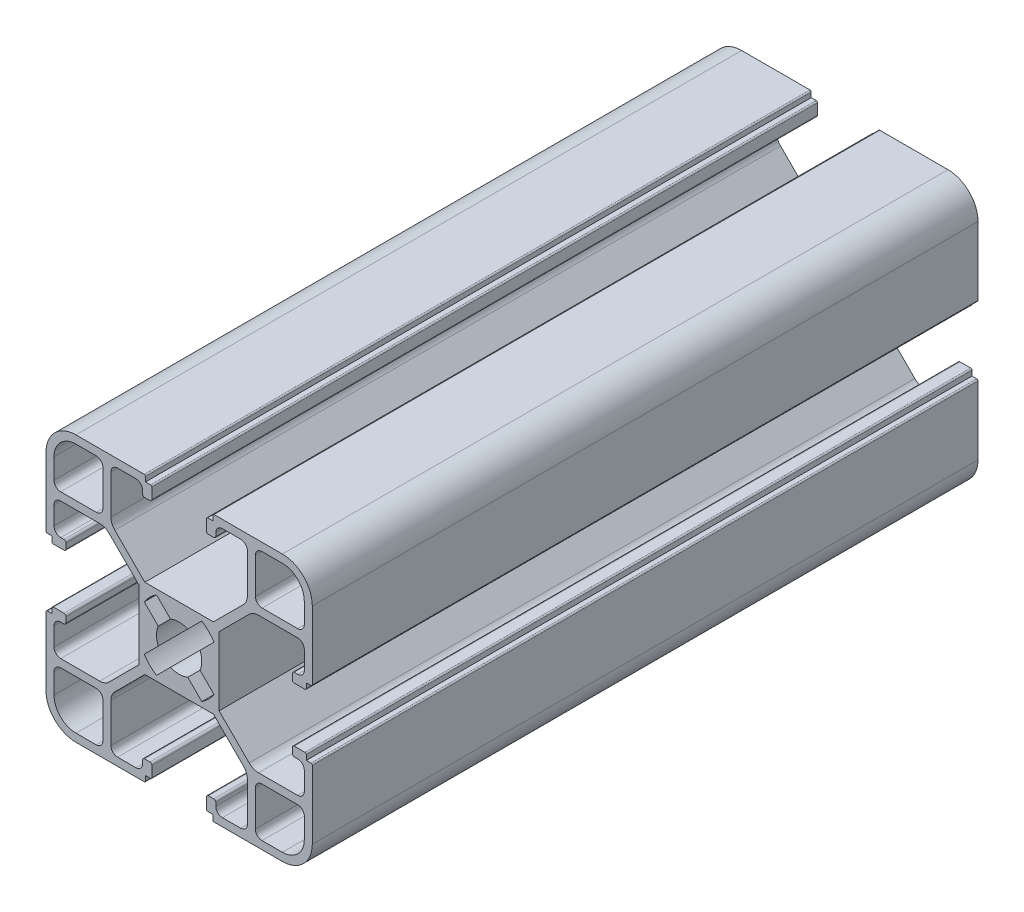
SolidWorks part; units mm, degrees
ref_plane "前视基准面" through (0, 0, 0) normal (0, 0, 1) x (1, 0, 0)
ref_plane "上视基准面" through (0, 0, 0) normal (0, 1, 0) x (1, 0, 0)
ref_plane "右视基准面" through (0, 0, 0) normal (1, 0, 0) x (0, 0, -1)
sketch "草图1" plane through (0, 0, 0) normal (0, 0, 1) x (1, 0, 0)
  line L0 (-5.5744, -5.6057) -> (-10.0871, -10.1184)
  line L1 (-5.5744, 4.6973) -> (-10.0871, 9.21)
  line L2 (-17.3744, -10.7042) -> (-11.5013, -10.7042)
  line L3 (-17.3744, 9.7958) -> (-11.5013, 9.7958)
  line L4 (-18.3744, -9.7042) -> (-18.3744, -6.9542)
  line L5 (-18.3744, 8.7958) -> (-18.3744, 6.0458)
  line L6 (-17.3744, -5.9542) -> (-16.8744, -5.9542)
  line L7 (-17.3744, 5.0458) -> (-16.8744, 5.0458)
  line L8 (-16.5744, -4.8542) -> (-16.5744, -5.6542)
  line L9 (-16.5744, 3.9458) -> (-16.5744, 4.7458)
  line L10 (-18.4744, -4.5542) -> (-16.8744, -4.5542)
  line L11 (-18.4744, 3.6458) -> (-16.8744, 3.6458)
  line L12 (-18.6744, -5.5042) -> (-18.6744, -4.7542)
  line L13 (-18.6744, -5.5042) -> (-19.3744, -5.5042)
  line L14 (-18.6744, 3.8458) -> (-18.6744, 4.5958)
  line L15 (-18.6744, 4.5958) -> (-19.3744, 4.5958)
  line L16 (-19.5744, -15.9542) -> (-19.5744, -5.7042)
  line L17 (-19.5744, 15.0458) -> (-19.5744, 4.7958)
  line L18 (-4.8244, -20.4542) -> (-15.0744, -20.4542)
  line L19 (-4.8244, 19.5458) -> (-15.0744, 19.5458)
  line L20 (-4.6244, -19.5542) -> (-4.6244, -20.2542)
  line L21 (-3.8744, -19.5542) -> (-4.6244, -19.5542)
  line L22 (-4.6244, 18.6458) -> (-4.6244, 19.3458)
  line L23 (-3.8744, 18.6458) -> (-4.6244, 18.6458)
  line L24 (-3.6744, -17.7542) -> (-3.6744, -19.3542)
  line L25 (-3.6744, 16.8458) -> (-3.6744, 18.4458)
  line L26 (-4.7744, -17.4542) -> (-3.9744, -17.4542)
  line L27 (-4.7744, 16.5458) -> (-3.9744, 16.5458)
  line L28 (-5.0744, -17.7542) -> (-5.0744, -18.2542)
  line L29 (-5.0744, 16.8458) -> (-5.0744, 17.3458)
  line L30 (-6.0744, -19.2542) -> (-8.8244, -19.2542)
  line L31 (-6.0744, 18.3458) -> (-8.8244, 18.3458)
  line L32 (-9.8244, -12.3812) -> (-9.8244, -18.2542)
  line L33 (-9.8244, 11.4727) -> (-9.8244, 17.3458)
  line L34 (-9.2386, -10.9669) -> (-4.7259, -6.4542)
  line L35 (-9.2386, 10.0585) -> (-4.7259, 5.5458)
  line L36 (10.0898, -10.9669) -> (5.5771, -6.4542)
  line L37 (10.0898, 10.0585) -> (5.5771, 5.5458)
  line L38 (10.6756, -12.3812) -> (10.6756, -18.2542)
  line L39 (10.6756, 11.4727) -> (10.6756, 17.3458)
  line L40 (6.9256, -19.2542) -> (9.6756, -19.2542)
  line L41 (6.9256, 18.3458) -> (9.6756, 18.3458)
  line L42 (5.9256, -17.7542) -> (5.9256, -18.2542)
  line L43 (5.9256, 16.8458) -> (5.9256, 17.3458)
  line L44 (5.6256, -17.4542) -> (4.8256, -17.4542)
  line L45 (5.6256, 16.5458) -> (4.8256, 16.5458)
  line L46 (4.5256, -17.7542) -> (4.5256, -19.3542)
  line L47 (4.5256, 16.8458) -> (4.5256, 18.4458)
  line L48 (5.4756, -19.5542) -> (4.7256, -19.5542)
  line L49 (5.4756, -19.5542) -> (5.4756, -20.2542)
  line L50 (5.4756, 18.6458) -> (4.7256, 18.6458)
  line L51 (5.4756, 18.6458) -> (5.4756, 19.3458)
  line L52 (5.6756, -20.4542) -> (15.9256, -20.4542)
  line L53 (5.6756, 19.5458) -> (15.9256, 19.5458)
  line L54 (20.4256, -15.9542) -> (20.4256, -5.7042)
  line L55 (20.4256, 15.0458) -> (20.4256, 4.7958)
  line L56 (19.5256, -5.5042) -> (20.2256, -5.5042)
  line L57 (19.5256, -5.5042) -> (19.5256, -4.7542)
  line L58 (19.5256, 4.5958) -> (20.2256, 4.5958)
  line L59 (19.5256, 3.8458) -> (19.5256, 4.5958)
  line L60 (19.3256, -4.5542) -> (17.7256, -4.5542)
  line L61 (19.3256, 3.6458) -> (17.7256, 3.6458)
  line L62 (17.4256, -4.8542) -> (17.4256, -5.6542)
  line L63 (17.4256, 3.9458) -> (17.4256, 4.7458)
  line L64 (18.2256, -5.9542) -> (17.7256, -5.9542)
  line L65 (18.2256, 5.0458) -> (17.7256, 5.0458)
  line L66 (19.2256, -9.7042) -> (19.2256, -6.9542)
  line L67 (19.2256, 8.7958) -> (19.2256, 6.0458)
  line L68 (18.2256, -10.7042) -> (12.3526, -10.7042)
  line L69 (18.2256, 9.7958) -> (12.3526, 9.7958)
  line L70 (6.4256, -5.6057) -> (10.9383, -10.1184)
  line L71 (6.4256, 4.6973) -> (10.9383, 9.21)
  line L72 (-15.0744, -19.2542) -> (-12.0244, -19.2542)
  line L73 (-11.0244, -18.2542) -> (-11.0244, -12.9042)
  line L74 (-12.0244, -11.9042) -> (-17.3744, -11.9042)
  line L75 (-18.3744, -12.9042) -> (-18.3744, -15.9542)
  line L76 (-12.0244, 18.3458) -> (-15.0744, 18.3458)
  line L77 (-18.3744, 15.0458) -> (-18.3744, 11.9958)
  line L78 (-17.3744, 10.9958) -> (-12.0244, 10.9958)
  line L79 (-11.0244, 11.9958) -> (-11.0244, 17.3458)
  line L80 (15.9256, 18.3458) -> (12.8756, 18.3458)
  line L81 (11.8756, 17.3458) -> (11.8756, 11.9958)
  line L82 (12.8756, 10.9958) -> (18.2256, 10.9958)
  line L83 (19.2256, 11.9958) -> (19.2256, 15.0458)
  line L84 (12.8756, -19.2542) -> (15.9256, -19.2542)
  line L85 (19.2256, -15.9542) -> (19.2256, -12.9042)
  line L86 (18.2256, -11.9042) -> (12.8756, -11.9042)
  line L87 (11.8756, -12.9042) -> (11.8756, -18.2542)
  line L88 (-4.7259, 5.5458) -> (5.5771, 5.5458)
  line L89 (-4.7259, -6.4542) -> (5.5771, -6.4542)
  line L90 (-5.5744, 4.6973) -> (-5.5744, -5.6057)
  line L91 (6.4256, 4.6973) -> (6.4256, -5.6057)
  line L92 (-2.9779, -5.6962) -> (-0.8766, -3.5949)
  line L93 (-4.8164, -3.8577) -> (-2.7151, -1.7565)
  line L94 (3.8291, -5.6962) -> (1.7279, -3.5949)
  line L95 (5.6676, -3.8577) -> (3.5663, -1.7565)
  line L96 (-2.9779, 4.7878) -> (-0.8766, 2.6865)
  line L97 (-4.8164, 2.9493) -> (-2.7151, 0.848)
  line L98 (3.8291, 4.7878) -> (1.7279, 2.6865)
  line L99 (5.6676, 2.9493) -> (3.5663, 0.848)
  arc A0 (-11.5013, -10.7042) -> (-10.0871, -10.1184) centre (-11.5013, -8.7042) ccw
  arc A1 (-10.0871, 9.21) -> (-11.5013, 9.7958) centre (-11.5013, 7.7958) ccw
  arc A2 (-18.3744, -9.7042) -> (-17.3744, -10.7042) centre (-17.3744, -9.7042) ccw
  arc A3 (-17.3744, 9.7958) -> (-18.3744, 8.7958) centre (-17.3744, 8.7958) ccw
  arc A4 (-17.3744, -5.9542) -> (-18.3744, -6.9542) centre (-17.3744, -6.9542) ccw
  arc A5 (-18.3744, 6.0458) -> (-17.3744, 5.0458) centre (-17.3744, 6.0458) ccw
  arc A6 (-16.8744, -5.9542) -> (-16.5744, -5.6542) centre (-16.8744, -5.6542) ccw
  arc A7 (-16.5744, 4.7458) -> (-16.8744, 5.0458) centre (-16.8744, 4.7458) ccw
  arc A8 (-16.5744, -4.8542) -> (-16.8744, -4.5542) centre (-16.8744, -4.8542) ccw
  arc A9 (-16.8744, 3.6458) -> (-16.5744, 3.9458) centre (-16.8744, 3.9458) ccw
  arc A10 (-18.4744, -4.5542) -> (-18.6744, -4.7542) centre (-18.4744, -4.7542) ccw
  arc A11 (-18.6744, 3.8458) -> (-18.4744, 3.6458) centre (-18.4744, 3.8458) ccw
  arc A12 (-19.3744, -5.5042) -> (-19.5744, -5.7042) centre (-19.3744, -5.7042) ccw
  arc A13 (-19.5744, 4.7958) -> (-19.3744, 4.5958) centre (-19.3744, 4.7958) ccw
  arc A14 (-19.5744, -15.9542) -> (-15.0744, -20.4542) centre (-15.0744, -15.9542) ccw
  arc A15 (-15.0744, 19.5458) -> (-19.5744, 15.0458) centre (-15.0744, 15.0458) ccw
  arc A16 (-4.8244, -20.4542) -> (-4.6244, -20.2542) centre (-4.8244, -20.2542) ccw
  arc A17 (-4.6244, 19.3458) -> (-4.8244, 19.5458) centre (-4.8244, 19.3458) ccw
  arc A18 (-3.8744, -19.5542) -> (-3.6744, -19.3542) centre (-3.8744, -19.3542) ccw
  arc A19 (-3.6744, 18.4458) -> (-3.8744, 18.6458) centre (-3.8744, 18.4458) ccw
  arc A20 (-3.6744, -17.7542) -> (-3.9744, -17.4542) centre (-3.9744, -17.7542) ccw
  arc A21 (-3.9744, 16.5458) -> (-3.6744, 16.8458) centre (-3.9744, 16.8458) ccw
  arc A22 (-4.7744, -17.4542) -> (-5.0744, -17.7542) centre (-4.7744, -17.7542) ccw
  arc A23 (-5.0744, 16.8458) -> (-4.7744, 16.5458) centre (-4.7744, 16.8458) ccw
  arc A24 (-6.0744, -19.2542) -> (-5.0744, -18.2542) centre (-6.0744, -18.2542) ccw
  arc A25 (-5.0744, 17.3458) -> (-6.0744, 18.3458) centre (-6.0744, 17.3458) ccw
  arc A26 (-9.8244, -18.2542) -> (-8.8244, -19.2542) centre (-8.8244, -18.2542) ccw
  arc A27 (-8.8244, 18.3458) -> (-9.8244, 17.3458) centre (-8.8244, 17.3458) ccw
  arc A28 (-9.2386, -10.9669) -> (-9.8244, -12.3812) centre (-7.8244, -12.3812) ccw
  arc A29 (-9.8244, 11.4727) -> (-9.2386, 10.0585) centre (-7.8244, 11.4727) ccw
  arc A30 (10.6756, -12.3812) -> (10.0898, -10.9669) centre (8.6756, -12.3812) ccw
  arc A31 (10.0898, 10.0585) -> (10.6756, 11.4727) centre (8.6756, 11.4727) ccw
  arc A32 (9.6756, -19.2542) -> (10.6756, -18.2542) centre (9.6756, -18.2542) ccw
  arc A33 (10.6756, 17.3458) -> (9.6756, 18.3458) centre (9.6756, 17.3458) ccw
  arc A34 (5.9256, -18.2542) -> (6.9256, -19.2542) centre (6.9256, -18.2542) ccw
  arc A35 (6.9256, 18.3458) -> (5.9256, 17.3458) centre (6.9256, 17.3458) ccw
  arc A36 (5.9256, -17.7542) -> (5.6256, -17.4542) centre (5.6256, -17.7542) ccw
  arc A37 (5.6256, 16.5458) -> (5.9256, 16.8458) centre (5.6256, 16.8458) ccw
  arc A38 (4.8256, -17.4542) -> (4.5256, -17.7542) centre (4.8256, -17.7542) ccw
  arc A39 (4.5256, 16.8458) -> (4.8256, 16.5458) centre (4.8256, 16.8458) ccw
  arc A40 (4.5256, -19.3542) -> (4.7256, -19.5542) centre (4.7256, -19.3542) ccw
  arc A41 (4.7256, 18.6458) -> (4.5256, 18.4458) centre (4.7256, 18.4458) ccw
  arc A42 (5.4756, -20.2542) -> (5.6756, -20.4542) centre (5.6756, -20.2542) ccw
  arc A43 (5.6756, 19.5458) -> (5.4756, 19.3458) centre (5.6756, 19.3458) ccw
  arc A44 (15.9256, -20.4542) -> (20.4256, -15.9542) centre (15.9256, -15.9542) ccw
  arc A45 (20.4256, 15.0458) -> (15.9256, 19.5458) centre (15.9256, 15.0458) ccw
  arc A46 (20.4256, -5.7042) -> (20.2256, -5.5042) centre (20.2256, -5.7042) ccw
  arc A47 (20.2256, 4.5958) -> (20.4256, 4.7958) centre (20.2256, 4.7958) ccw
  arc A48 (19.5256, -4.7542) -> (19.3256, -4.5542) centre (19.3256, -4.7542) ccw
  arc A49 (19.3256, 3.6458) -> (19.5256, 3.8458) centre (19.3256, 3.8458) ccw
  arc A50 (17.7256, -4.5542) -> (17.4256, -4.8542) centre (17.7256, -4.8542) ccw
  arc A51 (17.4256, 3.9458) -> (17.7256, 3.6458) centre (17.7256, 3.9458) ccw
  arc A52 (17.4256, -5.6542) -> (17.7256, -5.9542) centre (17.7256, -5.6542) ccw
  arc A53 (17.7256, 5.0458) -> (17.4256, 4.7458) centre (17.7256, 4.7458) ccw
  arc A54 (19.2256, -6.9542) -> (18.2256, -5.9542) centre (18.2256, -6.9542) ccw
  arc A55 (18.2256, 5.0458) -> (19.2256, 6.0458) centre (18.2256, 6.0458) ccw
  arc A56 (18.2256, -10.7042) -> (19.2256, -9.7042) centre (18.2256, -9.7042) ccw
  arc A57 (19.2256, 8.7958) -> (18.2256, 9.7958) centre (18.2256, 8.7958) ccw
  arc A58 (10.9383, -10.1184) -> (12.3526, -10.7042) centre (12.3526, -8.7042) ccw
  arc A59 (12.3526, 9.7958) -> (10.9383, 9.21) centre (12.3526, 7.7958) ccw
  arc A60 (-12.0244, -19.2542) -> (-11.0244, -18.2542) centre (-12.0244, -18.2542) ccw
  arc A61 (-11.0244, -12.9042) -> (-12.0244, -11.9042) centre (-12.0244, -12.9042) ccw
  arc A62 (-17.3744, -11.9042) -> (-18.3744, -12.9042) centre (-17.3744, -12.9042) ccw
  arc A63 (-18.3744, -15.9542) -> (-15.0744, -19.2542) centre (-15.0744, -15.9542) ccw
  arc A64 (-15.0744, 18.3458) -> (-18.3744, 15.0458) centre (-15.0744, 15.0458) ccw
  arc A65 (-18.3744, 11.9958) -> (-17.3744, 10.9958) centre (-17.3744, 11.9958) ccw
  arc A66 (-12.0244, 10.9958) -> (-11.0244, 11.9958) centre (-12.0244, 11.9958) ccw
  arc A67 (-11.0244, 17.3458) -> (-12.0244, 18.3458) centre (-12.0244, 17.3458) ccw
  arc A68 (12.8756, 18.3458) -> (11.8756, 17.3458) centre (12.8756, 17.3458) ccw
  arc A69 (11.8756, 11.9958) -> (12.8756, 10.9958) centre (12.8756, 11.9958) ccw
  arc A70 (18.2256, 10.9958) -> (19.2256, 11.9958) centre (18.2256, 11.9958) ccw
  arc A71 (19.2256, 15.0458) -> (15.9256, 18.3458) centre (15.9256, 15.0458) ccw
  arc A72 (15.9256, -19.2542) -> (19.2256, -15.9542) centre (15.9256, -15.9542) ccw
  arc A73 (19.2256, -12.9042) -> (18.2256, -11.9042) centre (18.2256, -12.9042) ccw
  arc A74 (12.8756, -11.9042) -> (11.8756, -12.9042) centre (12.8756, -12.9042) ccw
  arc A75 (11.8756, -18.2542) -> (12.8756, -19.2542) centre (12.8756, -18.2542) ccw
  arc A76 (-4.8164, -3.8577) -> (-2.9779, -5.6962) centre (0.4256, -0.4542) ccw
  arc A77 (-0.8766, -3.5949) -> (1.7279, -3.5949) centre (0.4256, -0.4542) ccw
  arc A78 (3.5663, -1.7565) -> (3.5663, 0.848) centre (0.4256, -0.4542) ccw
  arc A79 (1.7279, 2.6865) -> (-0.8766, 2.6865) centre (0.4256, -0.4542) ccw
  arc A80 (-2.7151, 0.848) -> (-2.7151, -1.7565) centre (0.4256, -0.4542) ccw
  arc A81 (3.8291, -5.6962) -> (5.6676, -3.8577) centre (0.4256, -0.4542) ccw
  arc A82 (-2.9779, 4.7878) -> (-4.8164, 2.9493) centre (0.4256, -0.4542) ccw
  arc A83 (5.6676, 2.9493) -> (3.8291, 4.7878) centre (0.4256, -0.4542) ccw
extrude "凸台-拉伸1" add sketch "草图1" along normal blind 100
